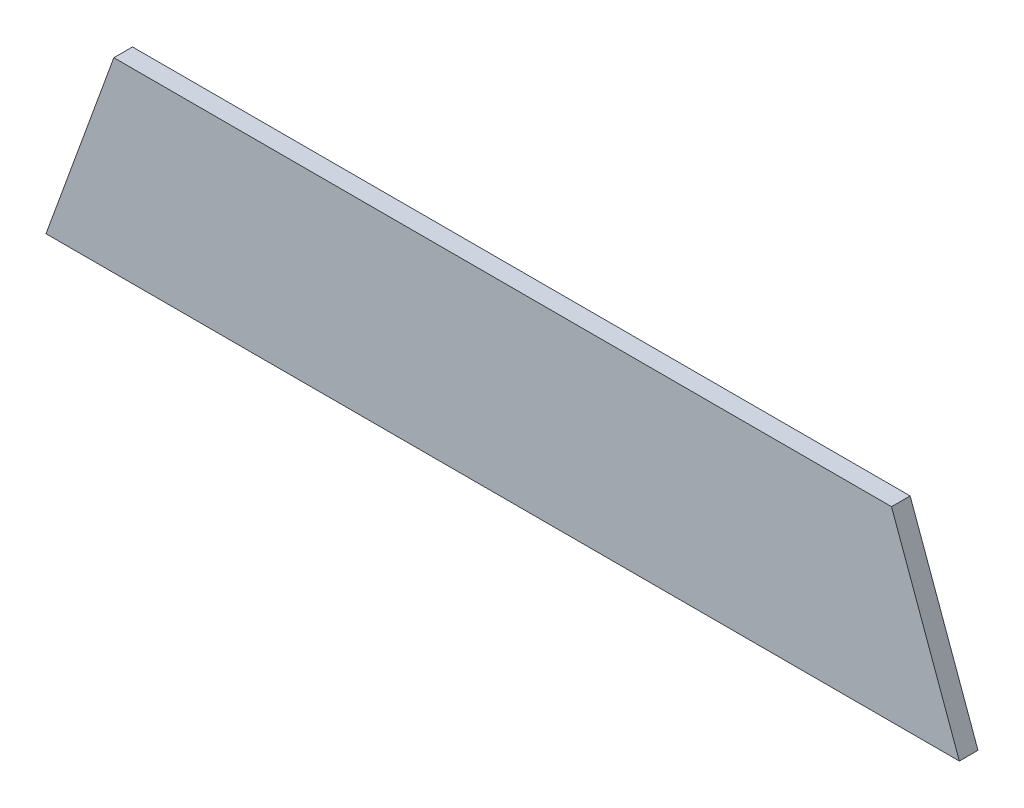
SolidWorks part; units mm, degrees
material "1060 Alloy"
ref_plane "Front Plane" through (0, 0, 0) normal (0, 0, 1) x (1, 0, 0)
ref_plane "Top Plane" through (0, 0, 0) normal (0, 1, 0) x (1, 0, 0)
ref_plane "Right Plane" through (0, 0, 0) normal (1, 0, 0) x (0, 0, -1)
sketch "Sketch1" plane through (0, 0, 0) normal (0, 0, 1) x (1, 0, 0)
  line L1 (-49.28, -10) -> (49.28, -10)
  line L2 (-49.28, -10) -> (-37.733, 10)
  line L3 (-37.733, 10) -> (37.733, 10)
  line L4 (49.28, -10) -> (37.733, 10)
  point P0 (0, 0)
  point P6 (0, 10)
  point P7 (0, -10)
  point P8 (22.7547, -10.4398)
  dimension "D1" = 98.56
  dimension "D2" = 20
  dimension "D3" = 60
sketch "Sketch2" plane through (0, 0, 0) normal (0, 0, 1) x (1, 0, 0)
  line L1 (-49.28, -10) -> (48.72, -10)
  line L2 (-49.28, -10) -> (-42.0006, 10)
  line L3 (-42.0006, 10) -> (41.4406, 10)
  line L4 (48.72, -10) -> (41.4406, 10)
  point P0 (-0.28, 0)
  point P6 (-0.28, 10)
  point P7 (-0.28, -10)
  point P8 (22.7547, -10.4398)
  dimension "D1" = 98
  dimension "D2" = 20
  dimension "D3" = 70
extrude "Boss-Extrude1" add sketch "Sketch2" along normal blind 2
sketch "Bend-Lines1" [suppressed] plane through (0, 0, 0) normal (0, 1, 0) x (1, 0, 0)
sketch "Bounding-Box1" [suppressed] plane through (0, 0, 0) normal (0, 1, 0) x (1, 0, 0)
